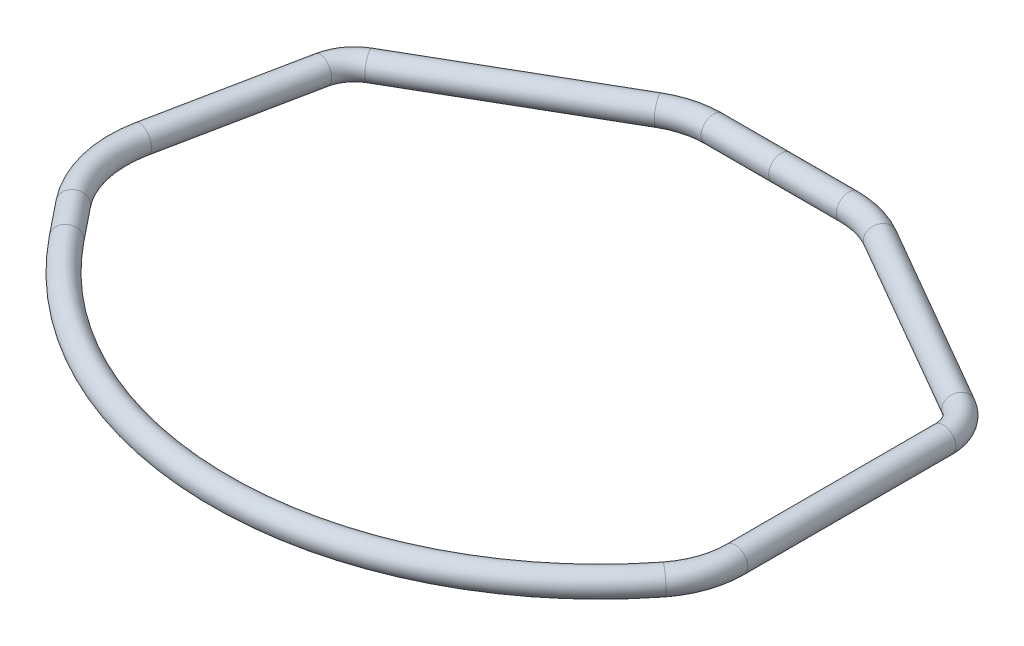
SolidWorks part; units mm, degrees
ref_plane "Front Plane" through (0, 0, 0) normal (0, 0, 1) x (1, 0, 0)
ref_plane "Top Plane" through (0, 0, 0) normal (0, 1, 0) x (1, 0, 0)
ref_plane "Right Plane" through (0, 0, 0) normal (1, 0, 0) x (0, 0, -1)
ref_plane "Plane1" through (0, -2.6401, 0) normal (0, -1, 0) x (-1, 0, 0)
sketch "Sketch1" plane through (0, -2.6401, 0) normal (0, -1, 0) x (-1, 0, 0)
  line L18 (83.3508, -38.9508) -> (90.9219, -29.5167)
  line L19 (97.1146, -4.0285) -> (88.5554, 38.2861)
  line L20 (82.9749, 46.0472) -> (31.22, 75.9279)
  line L21 (19.0587, 79.1865) -> (-19.0587, 79.1865)
  line L22 (-31.22, 75.9279) -> (-83.4857, 45.7523)
  line L23 (-89.297, 35.6869) -> (-89.297, -22.9797)
  arc A21 (90.9219, -29.5167) -> (97.1146, -4.0285) centre (66.802, -10.16) ccw
  arc A22 (88.5554, 38.2861) -> (82.9749, 46.0472) centre (77.1636, 35.9818) ccw
  arc A23 (31.22, 75.9279) -> (19.0587, 79.1865) centre (19.0587, 54.864) ccw
  arc A24 (-19.0587, 79.1865) -> (-31.22, 75.9279) centre (-19.0587, 54.864) ccw
  arc A25 (-83.4857, 45.7523) -> (-89.297, 35.6869) centre (-77.6745, 35.6869) ccw
  arc A26 (-89.297, -22.9797) -> (-84.1186, -37.9827) centre (-64.9745, -22.9797) ccw
  arc A27 (-84.1186, -37.9827) -> (83.3508, -38.9508) centre (0, 27.94) ccw
sketch "Sketch2" plane through (0, 0, 0) normal (1, 0, 0) x (0, 0, -1)
  circle A0 centre (79.1865, -2.6401) radius 3.4925
  dimension "D1" = 6.985
sweep "Sweep1" add profiles "Sketch2" path "Sketch1"
sketch "Sketch3" plane through (0, -2.6401, 0) normal (0, -1, 0) x (-1, 0, 0)
  line L0 (-29.4737, 72.9033) -> (-81.7395, 42.7277)
  line L1 (-85.232, 48.7769) -> (-32.9662, 78.9525)
  line L3 (-29.4737, 72.9033) -> (-81.7395, 42.7277)
  line L4 (0, 75.694) -> (-19.0587, 75.694)
  line L5 (-19.0587, 82.679) -> (0, 82.679)
  line L7 (0, 75.694) -> (-19.0587, 75.694)
  line L8 (19.0587, 75.694) -> (0, 75.694)
  line L9 (0, 82.679) -> (19.0587, 82.679)
  line L11 (19.0587, 75.694) -> (0, 75.694)
  line L12 (81.2286, 43.0226) -> (29.4737, 72.9033)
  line L13 (32.9662, 78.9525) -> (84.7211, 49.0718)
  line L15 (81.2286, 43.0226) -> (29.4737, 72.9033)
  line L16 (93.6914, -4.7209) -> (85.1322, 37.5937)
  line L17 (91.9786, 38.9785) -> (100.5378, -3.3361)
  line L19 (93.6914, -4.7209) -> (85.1322, 37.5937)
  line L20 (80.627, -36.7648) -> (88.198, -27.3308)
  line L21 (93.6457, -31.7026) -> (86.0747, -41.1367)
  line L23 (80.627, -36.7648) -> (88.198, -27.3308)
  line L24 (-85.8045, 35.6869) -> (-85.8045, -22.9797)
  line L25 (-92.7895, -22.9797) -> (-92.7895, 35.6869)
  line L27 (-85.8045, 35.6869) -> (-85.8045, -22.9797)
  arc A0 (-19.0587, 82.679) -> (-32.9662, 78.9525) centre (-19.0587, 54.864) ccw
  arc A1 (-19.0587, 75.694) -> (-29.4737, 72.9033) centre (-19.0587, 54.864) ccw
  arc A2 (-19.0587, 75.694) -> (-29.4737, 72.9033) centre (-19.0587, 54.864) ccw
  arc A4 (32.9662, 78.9525) -> (19.0587, 82.679) centre (19.0587, 54.864) ccw
  arc A5 (29.4737, 72.9033) -> (19.0587, 75.694) centre (19.0587, 54.864) ccw
  arc A6 (29.4737, 72.9033) -> (19.0587, 75.694) centre (19.0587, 54.864) ccw
  arc A8 (91.9786, 38.9785) -> (84.7211, 49.0718) centre (77.1636, 35.9818) ccw
  arc A9 (85.1322, 37.5937) -> (81.2286, 43.0226) centre (77.1636, 35.9818) ccw
  arc A10 (85.1322, 37.5937) -> (81.2286, 43.0226) centre (77.1636, 35.9818) ccw
  arc A12 (93.6457, -31.7026) -> (100.5378, -3.3361) centre (66.802, -10.16) ccw
  arc A13 (88.198, -27.3308) -> (93.6914, -4.7209) centre (66.802, -10.16) ccw
  arc A14 (88.198, -27.3308) -> (93.6914, -4.7209) centre (66.802, -10.16) ccw
  arc A16 (-86.8675, -40.137) -> (86.0747, -41.1367) centre (0, 27.94) ccw
  arc A17 (-81.3696, -35.8284) -> (80.627, -36.7648) centre (0, 27.94) ccw
  arc A18 (-81.3696, -35.8284) -> (80.627, -36.7648) centre (0, 27.94) ccw
  arc A20 (-92.7895, -22.9797) -> (-86.8675, -40.137) centre (-64.9745, -22.9797) ccw
  arc A21 (-85.8045, -22.9797) -> (-81.3696, -35.8284) centre (-64.9745, -22.9797) ccw
  arc A22 (-85.8045, -22.9797) -> (-81.3696, -35.8284) centre (-64.9745, -22.9797) ccw
  arc A24 (-85.232, 48.7769) -> (-92.7895, 35.6869) centre (-77.6745, 35.6869) ccw
  arc A25 (-81.7395, 42.7277) -> (-85.8045, 35.6869) centre (-77.6745, 35.6869) ccw
  arc A26 (-81.7395, 42.7277) -> (-85.8045, 35.6869) centre (-77.6745, 35.6869) ccw
